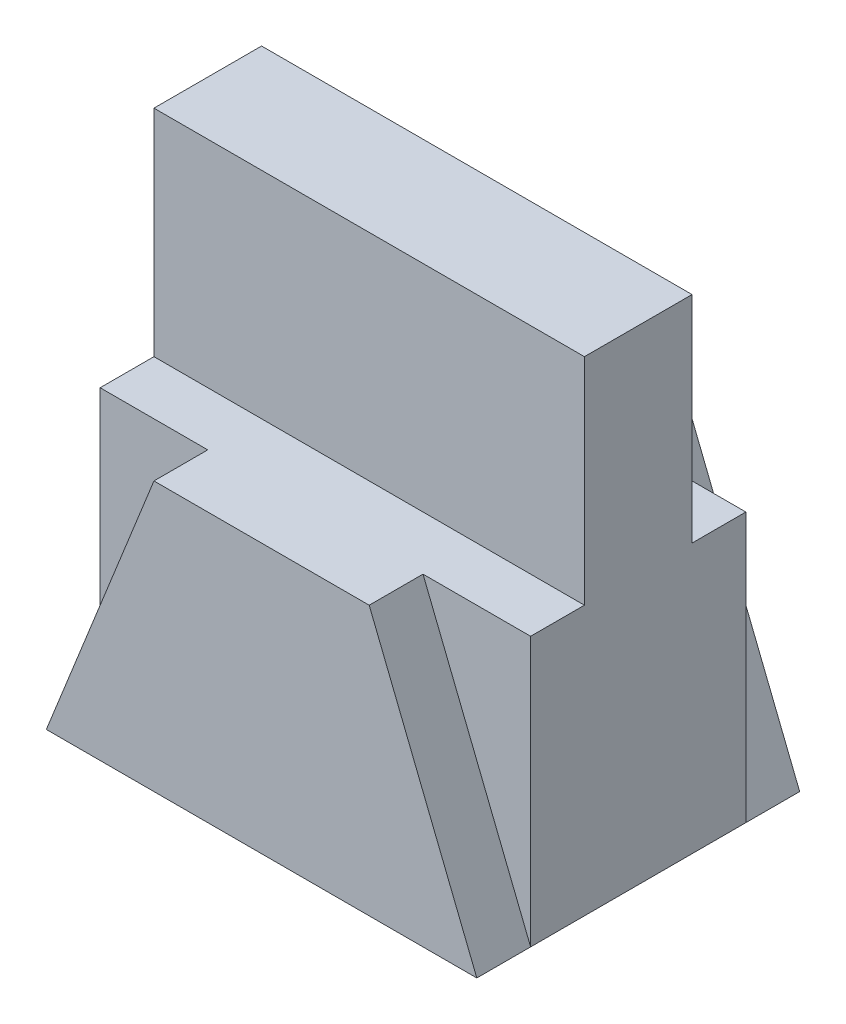
SolidWorks part; units mm, degrees
ref_plane "Alzado" through (0, 0, 0) normal (0, 0, 1) x (1, 0, 0)
ref_plane "Planta" through (0, 0, 0) normal (0, 1, 0) x (1, 0, 0)
ref_plane "Vista lateral" through (0, 0, 0) normal (1, 0, 0) x (0, 0, -1)
sketch "Croquis1" plane through (0, 0, 0) normal (1, 0, 0) x (0, 0, -1)
  line L0 (-15, 0) -> (15, 0)
  line L1 (15, 0) -> (15, 25)
  line L2 (15, 25) -> (5, 25)
  line L3 (5, 25) -> (5, 45)
  line L4 (5, 45) -> (-5, 45)
  line L5 (-5, 45) -> (-5, 25)
  line L6 (-5, 25) -> (-15, 25)
  line L7 (-15, 25) -> (-15, 0)
  point P3 (0, 0)
  point P10 (0, 45)
  dimension "D1" = 45
  dimension "D2" = 25
  dimension "D3" = 10
  dimension "D4" = 30
extrude "Saliente-Extruir1" add sketch "Croquis1" along normal mid plane 40
sketch "Croquis3" plane through (0, 0, 15) normal (0, 0, 1) x (1, 0, 0)
  line L0 (-20, 25) -> (-10, 25)
  line L1 (20, 25) -> (-20, 25) construction
  line L2 (-10, 25) -> (-20, 0)
  line L3 (-20, 0) -> (-20, 25)
  line L4 (10, 25) -> (20, 25)
  line L5 (20, 25) -> (20, 0)
  line L6 (20, 0) -> (10, 25)
  dimension "D1" = 20
extrude "Cortar-Extruir1" cut sketch "Croquis3" against normal blind 5
mirror "Simetría1" about plane through (0, 0, 0) normal (0, 0, 1) of "Cortar-Extruir1"
